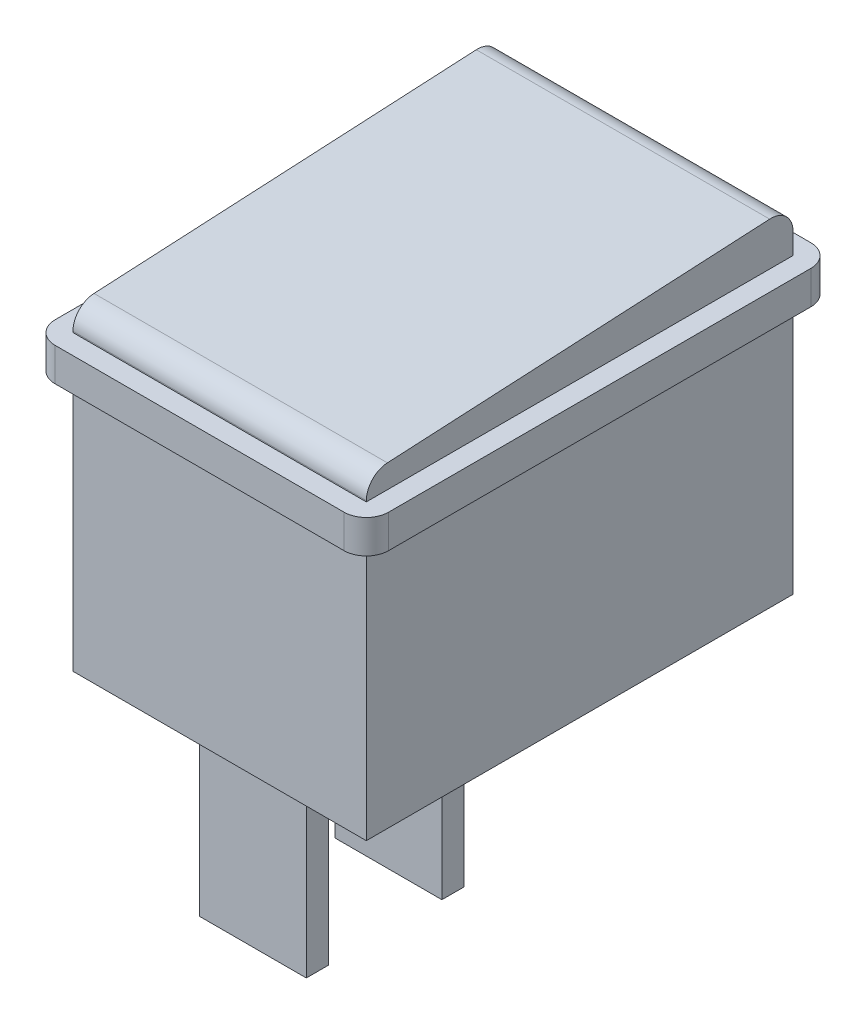
SolidWorks part; units mm, degrees
ref_plane "Front Plane" through (0, 0, 0) normal (0, 0, 1) x (1, 0, 0)
ref_plane "Top Plane" through (0, 0, 0) normal (0, 1, 0) x (1, 0, 0)
ref_plane "Right Plane" through (0, 0, 0) normal (1, 0, 0) x (0, 0, -1)
sketch "Sketch1" plane through (0, 0, 0) normal (0, 1, 0) x (1, 0, 0)
  line L1 (-6.6, -9.6) -> (6.6, -9.6)
  line L2 (-6.6, -9.6) -> (-6.6, 9.6)
  line L3 (-6.6, 9.6) -> (6.6, 9.6)
  line L4 (6.6, -9.6) -> (6.6, 9.6)
  line L5 (-6.6, -9.6) -> (6.6, 9.6) construction
  line L6 (-6.6, 9.6) -> (6.6, -9.6) construction
  point P0 (0, 0)
  dimension "D1" = 19.2
  dimension "D2" = 13.2
extrude "Boss-Extrude1" add sketch "Sketch1" along normal blind 11.7
sketch "Sketch2" plane through (0, 11.7, 0) normal (0, 1, 0) x (1, 0, 0)
  line L1 (-7.5, -10.5) -> (7.5, -10.5)
  line L2 (-7.5, -10.5) -> (-7.5, 10.5)
  line L3 (-7.5, 10.5) -> (7.5, 10.5)
  line L4 (7.5, -10.5) -> (7.5, 10.5)
  line L5 (-7.5, -10.5) -> (7.5, 10.5) construction
  line L6 (-7.5, 10.5) -> (7.5, -10.5) construction
  point P0 (0, 0)
  dimension "D1" = 21
  dimension "D2" = 15
extrude "Boss-Extrude2" add sketch "Sketch2" along normal blind 1.5
sketch "Sketch3" plane through (0, 13.2, 0) normal (0, 1, 0) x (1, 0, 0)
  line L1 (6.6, -9.6) -> (-6.6, -9.6)
  line L2 (6.6, -9.6) -> (6.6, 9.6)
  line L3 (6.6, 9.6) -> (-6.6, 9.6)
  line L4 (-6.6, -9.6) -> (-6.6, 9.6)
  line L5 (6.6, -9.6) -> (-6.6, 9.6) construction
  line L6 (6.6, 9.6) -> (-6.6, -9.6) construction
  point P0 (0, 0)
  dimension "D1" = 13.2
  dimension "D2" = 19.2
extrude "Boss-Extrude3" add sketch "Sketch3" along normal blind 5
sketch "Sketch4" plane through (6.6, 0, 0) normal (1, 0, 0) x (0, 0, -1)
  line L0 (-9.6, 18.2) -> (-9.6, 15.7)
  line L1 (9.6, 15.2) -> (-9.6, 14.2)
  line L2 (-9.6, 18.2) -> (-9.6, 13.2) construction
  line L5 (9.6, 18.2) -> (9.6, 13.2) construction
  line L6 (9.6, 15.2) -> (9.6, 18.2)
  line L7 (-9.6, 18.2) -> (9.6, 18.2) construction
  line L8 (9.6, 18.2) -> (-9.6, 18.2)
  line L9 (-9.6, 15.7) -> (-9.6, 14.2)
  point P2 (-9.6, 14.0721)
  dimension "D1" = 4
  dimension "D2" = 3
extrude "Cut-Extrude1" cut sketch "Sketch4" against normal up to surface (13.2 mm away) up to face at (-6.6, 15.7, 0)
sketch "Sketch5" plane through (0, 0, 0) normal (0, -1, 0) x (1, 0, 0)
  line L0 (0, 9.6) -> (0, -9.6) construction
  line L1 (-6.6, 9.6) -> (6.6, 9.6) construction
  line L2 (6.6, -9.6) -> (-6.6, -9.6) construction
  line L3 (-2.4, 2) -> (2.4, 2)
  line L4 (-2.4, 8.1) -> (2.4, 8.1)
  line L5 (-2.4, 8.1) -> (-2.4, 7.1)
  line L6 (-2.4, 7.1) -> (2.4, 7.1)
  line L7 (2.4, 8.1) -> (2.4, 7.1)
  line L8 (-2.4, 8.1) -> (2.4, 7.1) construction
  line L9 (-2.4, 7.1) -> (2.4, 8.1) construction
  line L10 (-2.4, 2) -> (-2.4, 1)
  line L11 (-2.4, 1) -> (2.4, 1)
  line L12 (2.4, 2) -> (2.4, 1)
  point P6 (0, 7.6)
  point P15 (0, 2)
  dimension "D1" = 4.8
  dimension "D2" = 1
  dimension "D3" = 1.5
  dimension "D4" = 1
  dimension "D5" = 4.8
  dimension "D6" = 7.1
extrude "Boss-Extrude4" add sketch "Sketch5" along normal blind 8.2
fillet "Fillet1" radius 1 6 edges at (-7.5, 12.45, 10.5) (-7.5, 12.45, -10.5) (7.5, 12.45, -10.5) (7.5, 12.45, 10.5) (0, 14.2, 9.6) (0, 15.2, -9.6)
